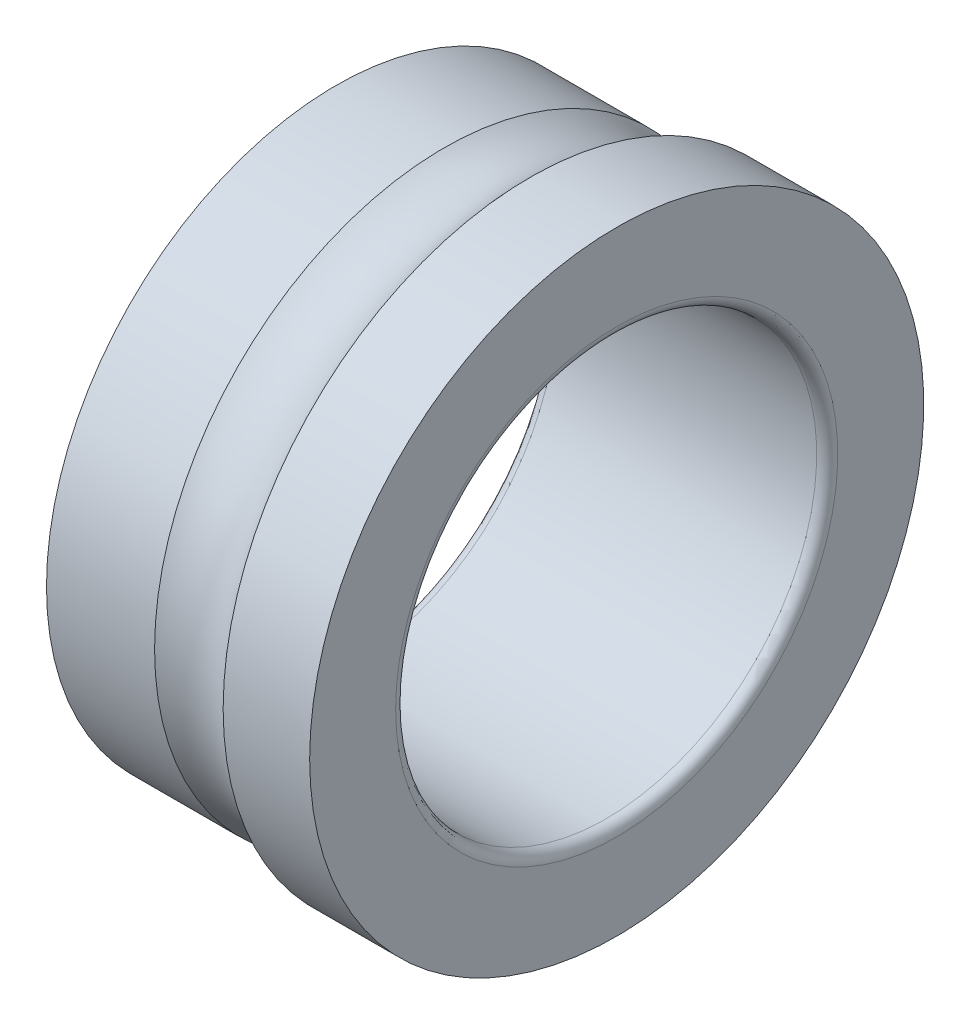
SolidWorks part; units mm, degrees
material "Chrome Stainless Steel"
ref_plane "Front Plane" through (0, 0, 0) normal (0, 0, 1) x (1, 0, 0)
ref_plane "Top Plane" through (0, 0, 0) normal (0, 1, 0) x (1, 0, 0)
ref_plane "Right Plane" through (0, 0, 0) normal (1, 0, 0) x (0, 0, -1)
ref_plane "Plane1" through (0, 0, 0) normal (0, 0, 1) x (1, 0, 0)
sketch "Sketch1" plane through (0, 0, 0) normal (0, 0, 1) x (1, 0, 0)
  line L0 (-3.7, 6) -> (3.7, 6)
  line L1 (4, 6.3) -> (4, 8.75)
  line L2 (4, 8.75) -> (1.5344, 8.75)
  line L3 (-0.9197, 8.25) -> (-4, 8.25)
  line L4 (-4, 8.25) -> (-4, 6.3)
  line L5 (4, 0) -> (-4, 0) construction
  arc A0 (-4, 6.3) -> (-3.7, 6) centre (-3.7, 6.3) ccw
  arc A1 (3.7, 6) -> (4, 6.3) centre (3.7, 6.3) ccw
  arc A2 (1.5344, 8.75) -> (-0.9197, 8.25) centre (0, 10.0085) cw
revolve "Revolve1" add sketch "Sketch1" angle 360 about L5
